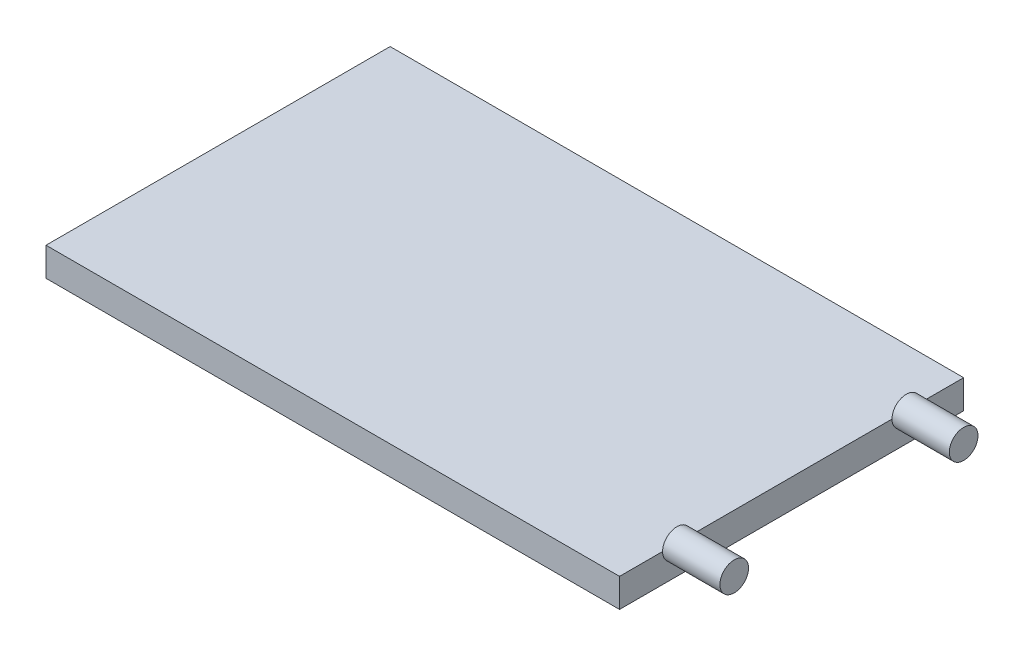
SolidWorks part; units mm, degrees
ref_plane "정면" through (0, 0, 0) normal (0, 0, 1) x (1, 0, 0)
ref_plane "윗면" through (0, 0, 0) normal (0, 1, 0) x (1, 0, 0)
ref_plane "우측면" through (0, 0, 0) normal (1, 0, 0) x (0, 0, -1)
sketch "스케치1" plane through (0, 0, 0) normal (0, 1, 0) x (1, 0, 0)
  line L1 (-5, 3) -> (5, 3)
  line L2 (-5, 3) -> (-5, -3)
  line L3 (-5, -3) -> (5, -3)
  line L4 (5, 3) -> (5, -3)
  line L5 (-5, 3) -> (5, -3) construction
  line L6 (-5, -3) -> (5, 3) construction
  point P0 (0, 0)
  dimension "D1" = 6
  dimension "D2" = 10
extrude "보스-돌출1" add sketch "스케치1" along normal blind 0.5
sketch "스케치2" plane through (5, 0, 0) normal (1, 0, 0) x (0, 0, -1)
  line L0 (-3, 0.5) -> (3, 0.5) construction
  line L1 (0, 0) -> (0, 0.5) construction
  circle A0 centre (-2, 0.5) radius 0.25
  circle A1 centre (2, 0.5) radius 0.25
  dimension "D1" = 0.5
  dimension "D2" = 2
extrude "보스-돌출2" add sketch "스케치2" along normal blind 1
